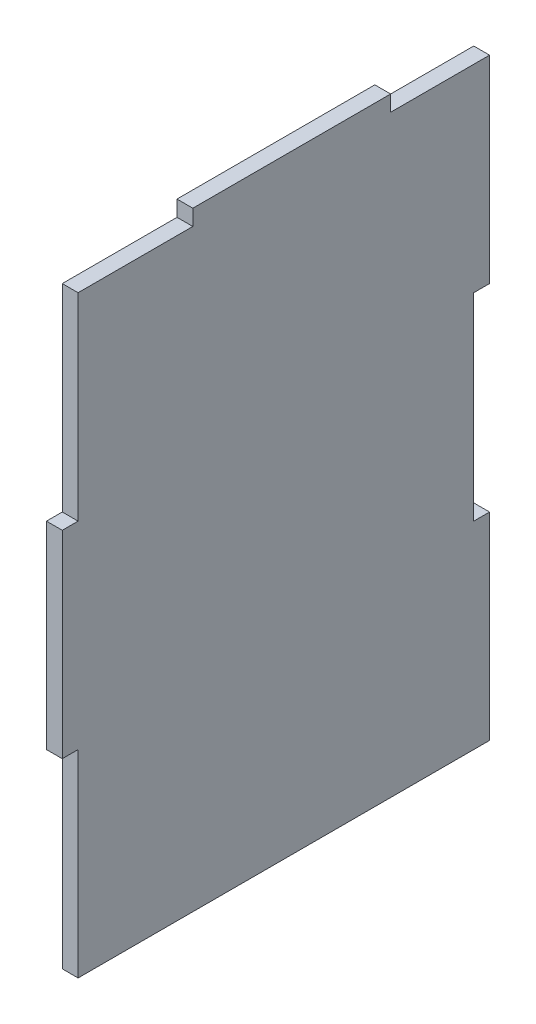
SolidWorks part; units mm, degrees
ref_plane "Front Plane" through (0, 0, 0) normal (0, 0, 1) x (1, 0, 0)
ref_plane "Top Plane" through (0, 0, 0) normal (0, 1, 0) x (1, 0, 0)
ref_plane "Right Plane" through (0, 0, 0) normal (1, 0, 0) x (0, 0, -1)
sketch "Sketch1" plane through (0, 0, 0) normal (1, 0, 0) x (0, 0, -1)
  line L0 (0, 0) -> (100, 0)
  line L1 (100, 0) -> (100, 50)
  line L5 (100, 100) -> (100, 150)
  line L6 (100, 150) -> (75, 150)
  line L10 (25, 150) -> (0, 150)
  line L16 (100, 100) -> (96, 100)
  line L17 (96, 100) -> (96, 50)
  line L18 (96, 50) -> (100, 50)
  line L19 (0, 150) -> (-4, 150)
  line L20 (-4, 121) -> (-4, 321) construction
  line L21 (-4, 150) -> (-4, 100)
  line L22 (-4, -4) -> (-4, 121) construction
  line L23 (-4, 100) -> (-8, 100)
  line L24 (-8, 0) -> (-8, 121) construction
  line L25 (-8, 100) -> (-8, 50)
  line L26 (-8, 50) -> (-4, 50)
  line L27 (-4, 50) -> (-4, 0)
  line L28 (-4, 0) -> (0, 0)
  line L29 (25, 150) -> (25, 154)
  line L30 (25, 154) -> (75, 154)
  line L31 (75, 154) -> (75, 150)
extrude "Boss-Extrude1" add sketch "Sketch1" along normal blind 4
